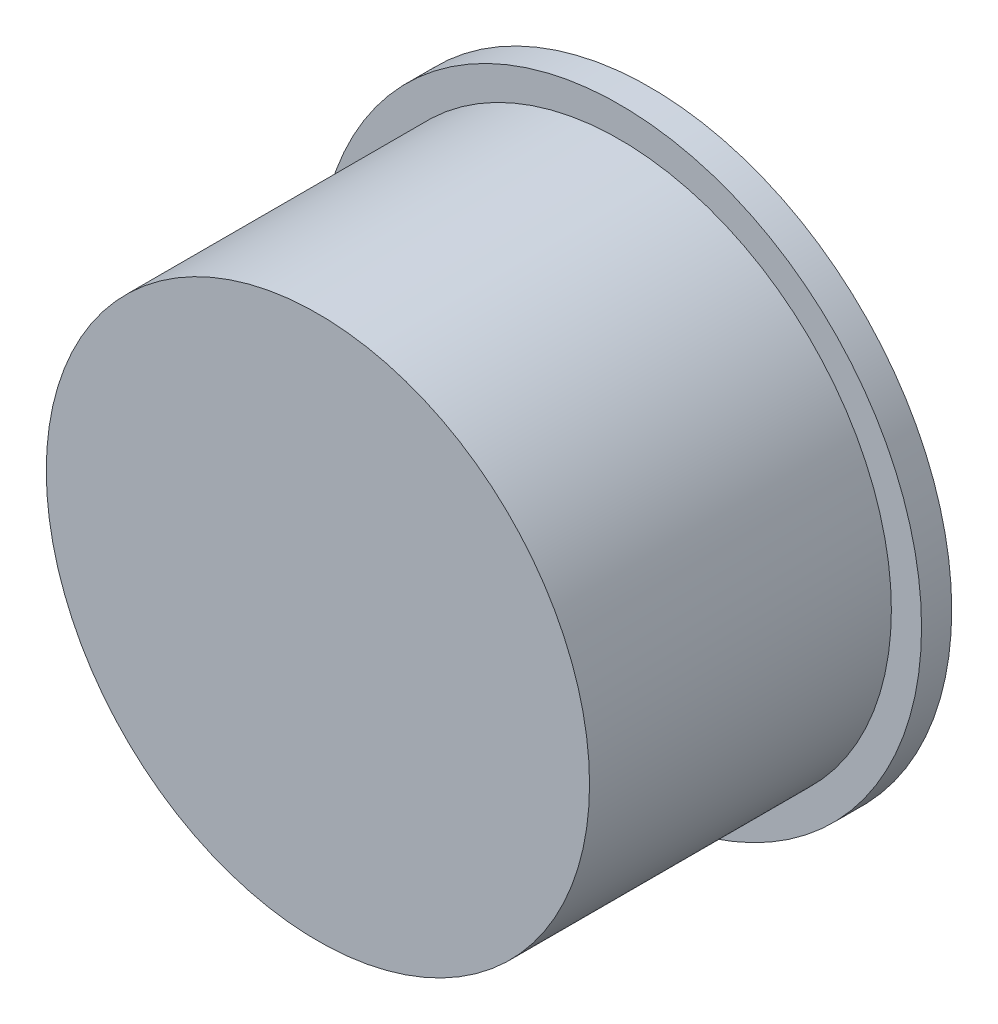
SolidWorks part; units mm, degrees
ref_plane "Front Plane" through (0, 0, 0) normal (0, 0, 1) x (1, 0, 0)
ref_plane "Top Plane" through (0, 0, 0) normal (0, 1, 0) x (1, 0, 0)
ref_plane "Right Plane" through (0, 0, 0) normal (1, 0, 0) x (0, 0, -1)
sketch "Sketch1" plane through (0, 0, 0) normal (0, 0, 1) x (1, 0, 0)
  circle A0 centre (0, 0) radius 17.78
extrude "Boss-Extrude1" add sketch "Sketch1" along normal blind 5.08
sketch "Sketch2" plane through (0, 0, 5.08) normal (0, 0, 1) x (1, 0, 0)
  circle A0 centre (0, 0) radius 50.8
extrude "Boss-Extrude2" add sketch "Sketch2" along normal blind 5.08
sketch "Sketch3" plane through (0, 0, 10.16) normal (0, 0, 1) x (1, 0, 0)
  circle A0 centre (0, 0) radius 45.72
extrude "Boss-Extrude3" add sketch "Sketch3" along normal blind 50.8
